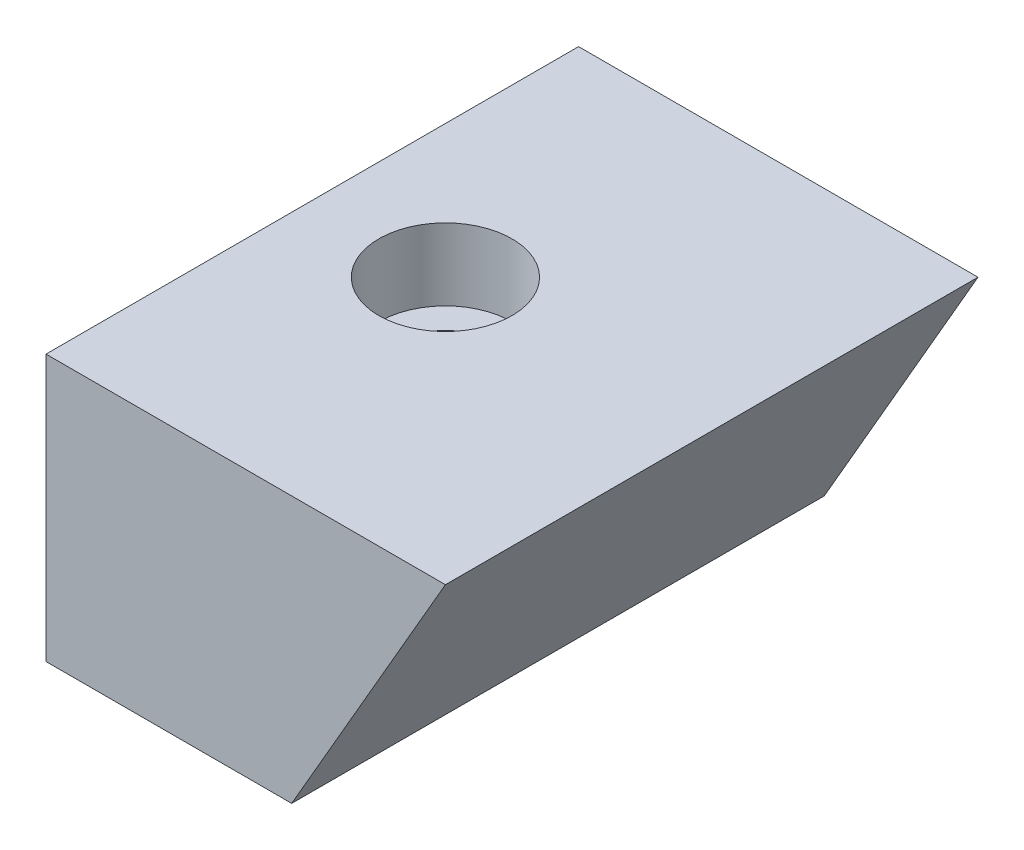
SolidWorks part; units mm, degrees
ref_plane "Plan de face" through (0, 0, 0) normal (0, 0, 1) x (1, 0, 0)
ref_plane "Plan de dessus" through (0, 0, 0) normal (0, 1, 0) x (1, 0, 0)
ref_plane "Plan de droite" through (0, 0, 0) normal (1, 0, 0) x (0, 0, -1)
sketch "Esquisse1" plane through (0, 0, 0) normal (0, 0, 1) x (1, 0, 0)
  line L0 (-10, 0.6912) -> (8.453, 0.6912)
  line L1 (8.453, 0.6912) -> (20, 20.6912)
  line L2 (20, 20.6912) -> (-10, 20.6912)
  line L3 (-10, 20.6912) -> (-10, 0.6912)
  line L4 (30, 0.6912) -> (-10, 0.6912) construction
  line L5 (-10, 0.6912) -> (-10, 15.6912) construction
  dimension "D1" = 30
  dimension "D2" = 60
  dimension "D3" = 20
extrude "Boss.-Extru.1" add sketch "Esquisse1" along normal blind 40
hole_wizard "Chambrage pour vis à tête hexagonale M51" positions "Esquisse2" profile "Esquisse3" counterbore size "M5" standard "ISO" end condition through all
sketch "Esquisse2" plane through (0, 20.6912, 0) normal (0, 1, 0) x (1, 0, 0)
  point P0 (0, -20)
sketch "Esquisse3" plane through (0, 20.6912, 20) normal (1, 0, 0) x (0, 0, 1)
  line L0 (0, 0) -> (0, 20)
  line L1 (0, 20) -> (2.75, 20)
  line L3 (2.75, 20) -> (2.75, 5.4)
  line L4 (2.75, 5.4) -> (5, 5.4)
  line L5 (5, 5.4) -> (5, 0)
  line L7 (5, 0) -> (0, 0)
  line L11 (0, -6.35) -> (0, 107.95) construction
  dimension "Diamètre du perçage jusqu'au prochain" = 5.5
  dimension "Profondeur du perçage jusqu'au prochain" = 20
  dimension "Diamètre du chambrage" = 10
  dimension "Profondeur du chambrage" = 5.4
